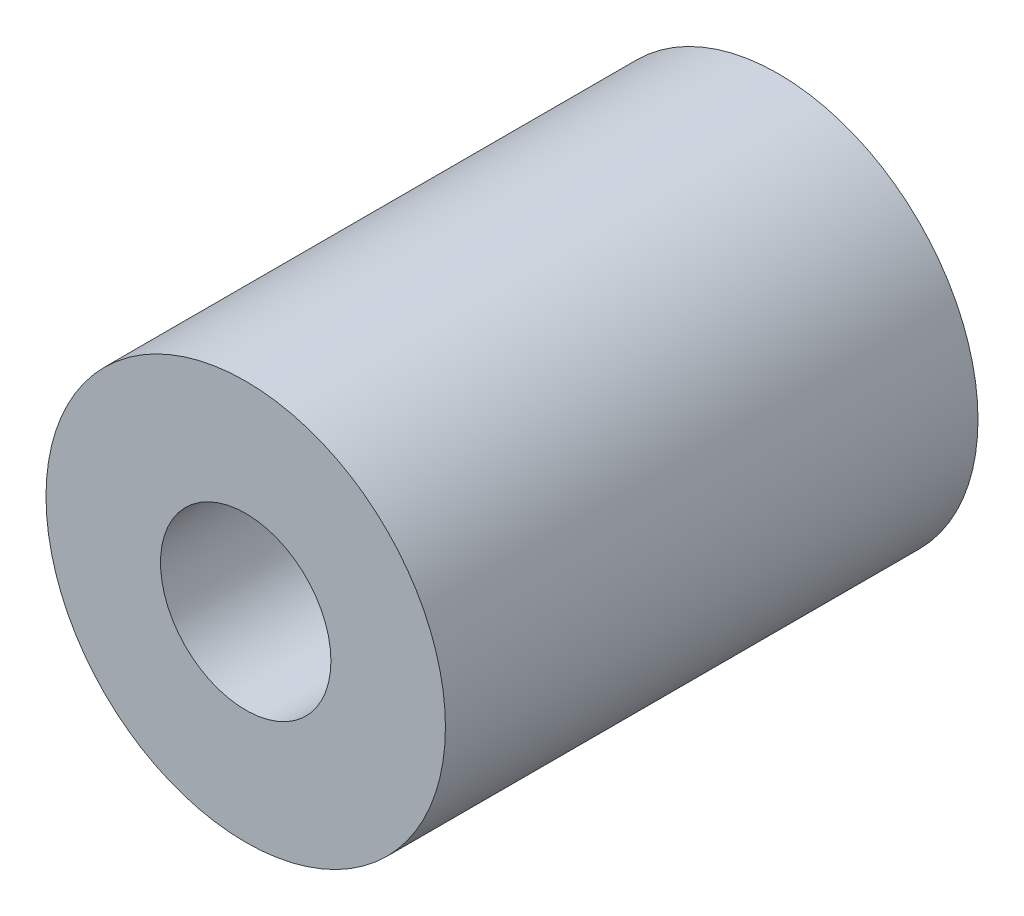
SolidWorks part; units mm, degrees
ref_plane "정면" through (0, 0, 0) normal (0, 0, 1) x (1, 0, 0)
ref_plane "윗면" through (0, 0, 0) normal (0, 1, 0) x (1, 0, 0)
ref_plane "우측면" through (0, 0, 0) normal (1, 0, 0) x (0, 0, -1)
sketch "스케치1" plane through (0, 0, 0) normal (0, 0, 1) x (1, 0, 0)
  circle A0 centre (0, 0) radius 3.2
  circle A1 centre (0, 0) radius 7.5
  dimension "D1" = 6.4
  dimension "D2" = 15
extrude "보스-돌출1" add sketch "스케치1" along normal blind 20
